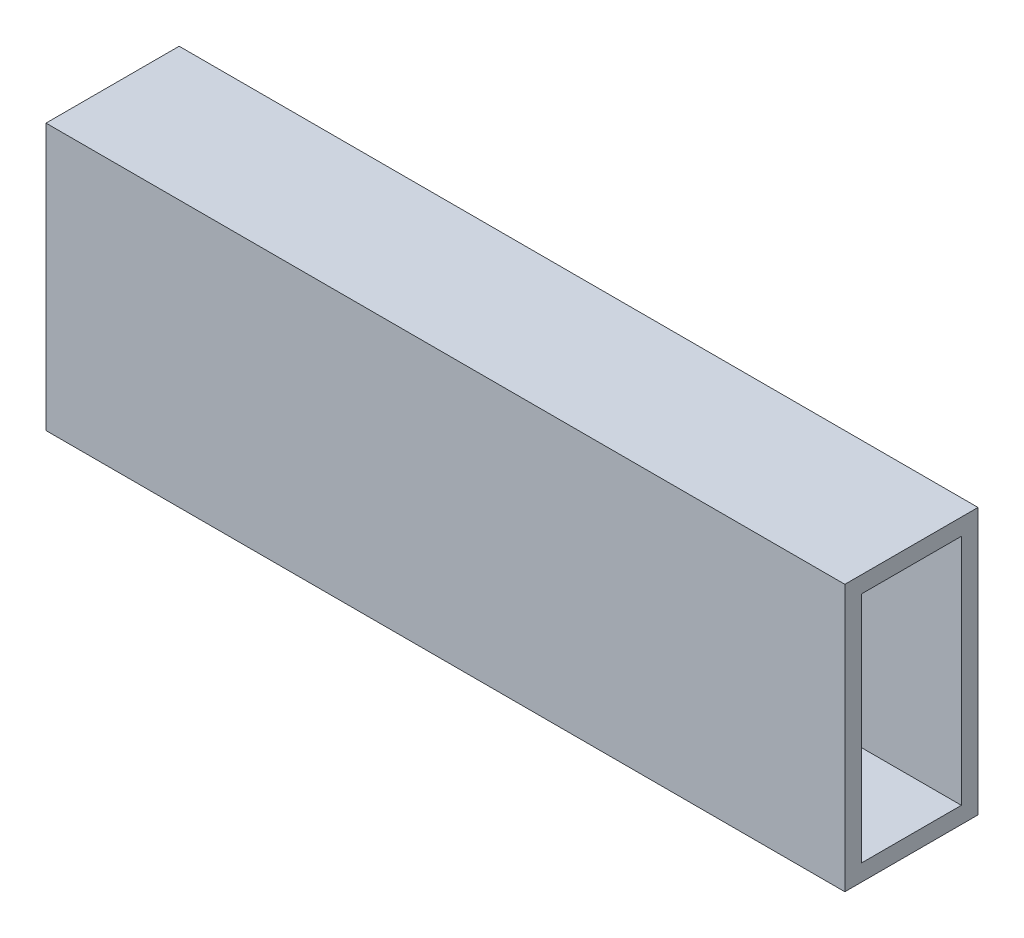
SolidWorks part; units mm, degrees
material "6061-T6 (SS)"
ref_plane "Front Plane" through (0, 0, 0) normal (0, 0, 1) x (1, 0, 0)
ref_plane "Top Plane" through (0, 0, 0) normal (0, 1, 0) x (1, 0, 0)
ref_plane "Right Plane" through (0, 0, 0) normal (1, 0, 0) x (0, 0, -1)
sketch "Sketch1" plane through (0, 0, 0) normal (1, 0, 0) x (0, 0, -1)
  line L1 (-12.7, -25.4) -> (12.7, -25.4)
  line L2 (-12.7, -25.4) -> (-12.7, 25.4)
  line L3 (-12.7, 25.4) -> (12.7, 25.4)
  line L4 (12.7, -25.4) -> (12.7, 25.4)
  line L5 (0, 25.4) -> (0, -25.4) construction
  line L6 (-12.7, 0) -> (12.7, 0) construction
  line L7 (-9.525, -22.225) -> (9.525, -22.225)
  line L8 (-9.525, -22.225) -> (-9.525, 22.225)
  line L9 (-9.525, 22.225) -> (9.525, 22.225)
  line L10 (9.525, -22.225) -> (9.525, 22.225)
  line L11 (0, 22.225) -> (0, -22.225) construction
  line L12 (-9.525, 0) -> (9.525, 0) construction
  point P0 (0, 0)
  point P4 (0, 0)
  dimension "D1" = 3.175
  dimension "D2" = 3.175
  dimension "D3" = 25.4
  dimension "D4" = 50.8
extrude "Boss-Extrude1" add sketch "Sketch1" along normal mid plane 152.4
